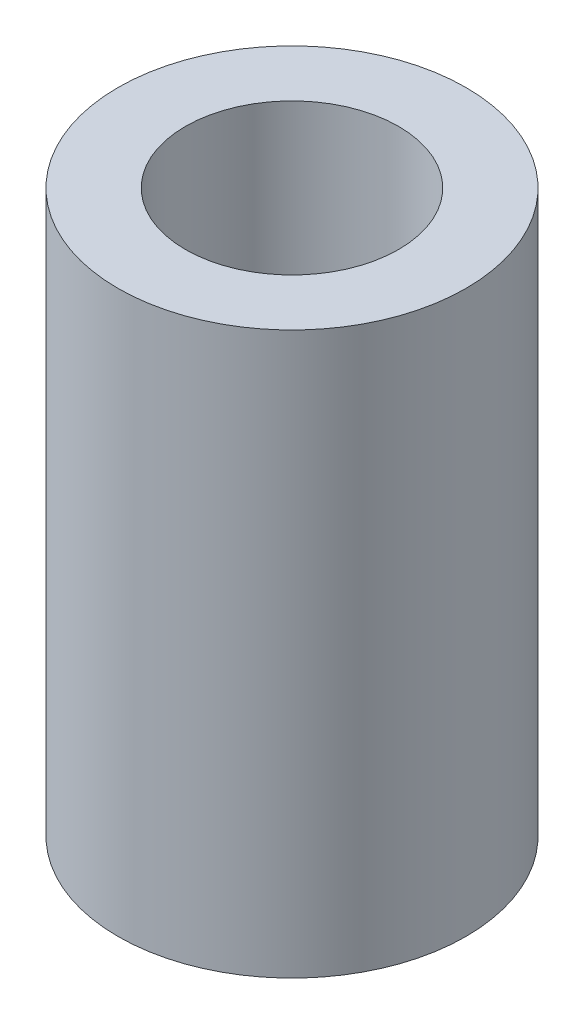
SolidWorks part; units mm, degrees
ref_plane "Alzado" through (0, 0, 0) normal (0, 0, 1) x (1, 0, 0)
ref_plane "Planta" through (0, 0, 0) normal (0, 1, 0) x (1, 0, 0)
ref_plane "Vista lateral" through (0, 0, 0) normal (1, 0, 0) x (0, 0, -1)
sketch "Croquis1" plane through (0, 0, 0) normal (0, 1, 0) x (1, 0, 0)
  circle A0 centre (0, 0) radius 7.75
  dimension "D1" = 15.5
extrude "Saliente-Extruir1" add sketch "Croquis1" along normal blind 25
shell "Vaciado1" thickness 3
sketch "Croquis2" plane through (0, 0, 0) normal (1, 0, 0) x (0, 0, -1)
  circle A0 centre (0, 4.1977) radius 2.3
  point P2 (0, 4.1977)
  dimension "D1" = 4.6
sketch "Croquis4" plane through (0, 0, 0) normal (0, -1, 0) x (1, 0, 0)
  circle A0 centre (0, 0) radius 7.75
extrude "Saliente-Extruir2" add sketch "Croquis4" against normal blind 8.7
sketch "Croquis3" plane through (0, 0, 0) normal (0, -1, 0) x (1, 0, 0)
  line L0 (-1.1238, 1.0676) -> (-1.1238, -1.0676)
  circle A0 centre (0, 0) radius 1.55
  dimension "D1" = 3.1
extrude "Cortar-Extruir1" cut sketch "Croquis3" against normal blind 36.6 contours L0 A0
extrude "Cortar-Extruir2" cut sketch "Croquis2" against normal blind 8.5
